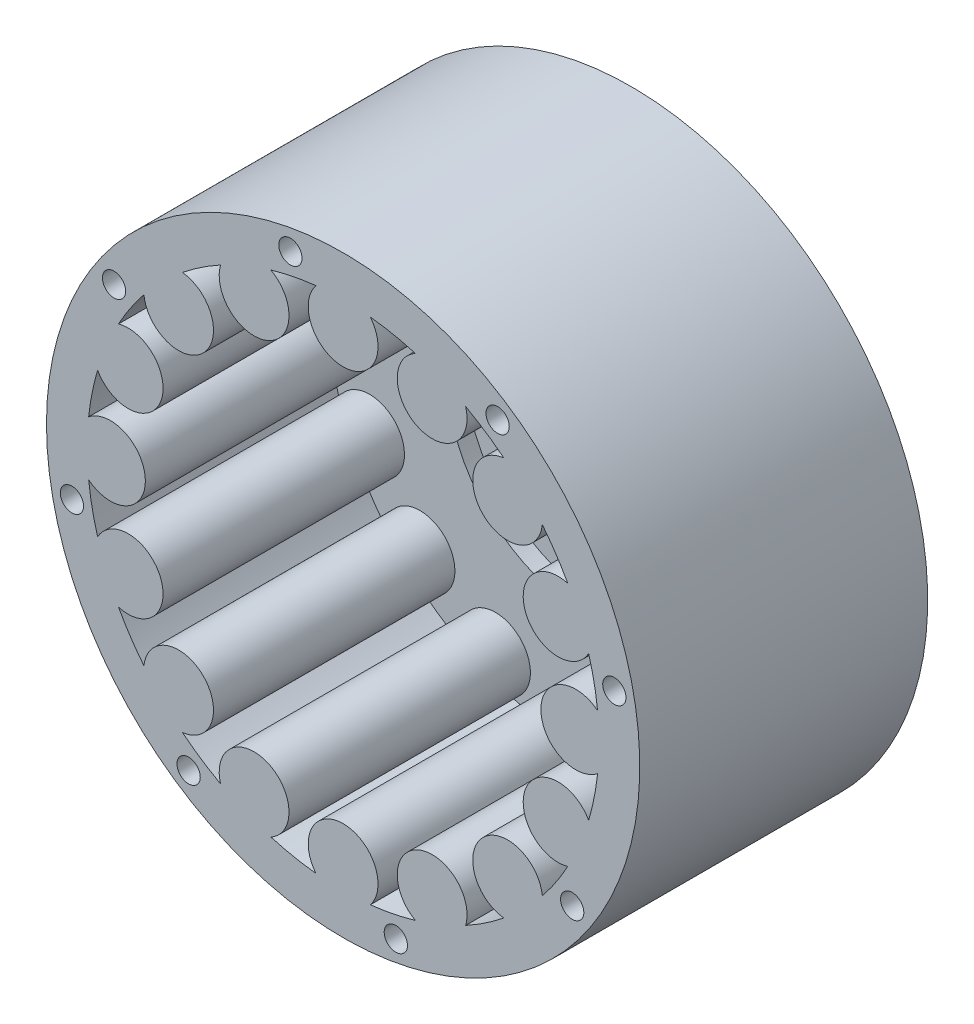
SolidWorks part; units mm, degrees
material "Custom Plastic"
ref_plane "Front Plane" through (0, 0, 0) normal (0, 0, 1) x (1, 0, 0)
ref_plane "Top Plane" through (0, 0, 0) normal (0, 1, 0) x (1, 0, 0)
ref_plane "Right Plane" through (0, 0, 0) normal (1, 0, 0) x (0, 0, -1)
sketch "Sketch1" plane through (0, 0, 0) normal (0, 0, 1) x (1, 0, 0)
  circle A2 centre (0, 0) radius 44
  dimension "D1" = 88
extrude "VolumeExtrude" add sketch "Sketch1" along normal blind 8
sketch "Sketch2" plane through (0, 0, 0) normal (0, 0, -1) x (-1, 0, 0)
  circle A1 centre (0, 0) radius 44 construction
  circle A2 centre (0, 0) radius 51
  circle A3 centre (0, 0) radius 51
  circle A4 centre (0, 0) radius 44
  dimension "D1" = 7
extrude "LipExtrude" add sketch "Sketch2" against normal blind 49.5
sketch "Sketch3" plane through (0, 0, 8) normal (0, 0, 1) x (1, 0, 0)
  circle A0 centre (0, 0) radius 40 construction
  circle A1 centre (0, 40) radius 6
  circle A2 centre (15.3073, 36.9552) radius 6
  circle A3 centre (28.2843, 28.2843) radius 6
  circle A4 centre (36.9552, 15.3073) radius 6
  circle A5 centre (40, 0) radius 6
  circle A6 centre (36.9552, -15.3073) radius 6
  circle A7 centre (28.2843, -28.2843) radius 6
  circle A8 centre (15.3073, -36.9552) radius 6
  circle A9 centre (0, -40) radius 6
  circle A10 centre (-15.3073, -36.9552) radius 6
  circle A11 centre (-28.2843, -28.2843) radius 6
  circle A12 centre (-36.9552, -15.3073) radius 6
  circle A13 centre (-40, 0) radius 6
  circle A14 centre (-36.9552, 15.3073) radius 6
  circle A15 centre (-28.2843, 28.2843) radius 6
  circle A16 centre (-15.3073, 36.9552) radius 6
  circle A18 centre (0, 0) radius 44 construction
  circle A19 centre (0, 0) radius 44 construction
  point P37 (0, 0)
  dimension "D1" = 80
  dimension "D2" = 12
  dimension "D3" = 16
extrude "EdgeCuts" [suppressed] cut sketch "Sketch3" along normal up to surface (24.5 mm away)
sketch "Sketch4" plane through (0, 0, 8) normal (0, 0, 1) x (1, 0, 0)
  circle A0 centre (0, 0) radius 18
  dimension "D1" = 36
extrude "Shaft Hole" cut sketch "Sketch4" against normal up to surface (8 mm away) contours A0 up to face at (-51, 0, 0)
sketch "Sketch5" [suppressed] plane through (0, 0, 7) normal (0, 0, 1) x (1, 0, 0)
  circle A0 centre (0, 0) radius 23.5
  dimension "D1" = 47
extrude "BearingHole" [suppressed] cut sketch "Sketch5" against normal blind 7
sketch "Sketch6" plane through (0, 0, 49.5) normal (0, 0, 1) x (1, 0, 0)
  line L0 (0, 0) -> (-9.0634, 46.6273) construction
  line L3 (0, 0) -> (25.3584, 0) construction
  circle A0 centre (-9.0634, 46.6273) radius 2
  circle A1 centre (26.5617, 39.3793) radius 2
  circle A2 centre (0, 0) radius 44 construction
  circle A3 centre (0, 0) radius 51 construction
  circle A4 centre (0, 0) radius 51 construction
  circle A5 centre (0, 0) radius 44 construction
  circle A13 centre (46.6273, 9.0634) radius 2
  circle A14 centre (39.3793, -26.5617) radius 2
  circle A15 centre (9.0634, -46.6273) radius 2
  circle A16 centre (-26.5617, -39.3793) radius 2
  circle A17 centre (-46.6273, -9.0634) radius 2
  circle A18 centre (-39.3793, 26.5617) radius 2
  point P23 (0, 0)
  point P31 (0, 0)
  dimension "D1" = 4
  dimension "D3" = 47.5
  dimension "D2" = 101
  dimension "D4" = 8
extrude "BoltHoles" cut sketch "Sketch6" against normal blind 6
sketch "Sketch7" plane through (0, 0, 8) normal (0, 0, 1) x (1, 0, 0)
  line L0 (0, 0) -> (0, 40) construction
  circle A0 centre (0, 40) radius 6
  circle A1 centre (15.3073, 36.9552) radius 6
  circle A2 centre (28.2843, 28.2843) radius 6
  circle A3 centre (36.9552, 15.3073) radius 6
  circle A4 centre (40, 0) radius 6
  circle A5 centre (36.9552, -15.3073) radius 6
  circle A6 centre (28.2843, -28.2843) radius 6
  circle A7 centre (15.3073, -36.9552) radius 6
  circle A8 centre (0, -40) radius 6
  circle A9 centre (-15.3073, -36.9552) radius 6
  circle A10 centre (-28.2843, -28.2843) radius 6
  circle A11 centre (-36.9552, -15.3073) radius 6
  circle A12 centre (-40, 0) radius 6
  circle A13 centre (-36.9552, 15.3073) radius 6
  circle A14 centre (-28.2843, 28.2843) radius 6
  circle A15 centre (-15.3073, 36.9552) radius 6
  point P36 (0, 0)
  dimension "D1" = 12
  dimension "D2" = 40
  dimension "D3" = 16
extrude "Boss-Extrude1" add sketch "Sketch7" along normal up to surface (41.5 mm away) up to face at (-7.0634, 46.6273, 49.5)
sketch "Sketch9" plane through (0, 0, 0) normal (0, 0, -1) x (-1, 0, 0)
  line L0 (0, 0) -> (-26.5617, 39.3793) construction
  line L1 (0, 0) -> (-52.3937, 0) construction
  circle A0 centre (0, 0) radius 47.5 construction
  circle A1 centre (-26.5617, 39.3793) radius 2.25
  circle A5 centre (39.3793, 26.5617) radius 2.25
  circle A6 centre (26.5617, -39.3793) radius 2.25
  circle A7 centre (-39.3793, -26.5617) radius 2.25
  circle A8 centre (-26.5617, 39.3793) radius 2 construction
  circle A9 centre (-26.5617, 39.3793) radius 2 construction
  point P12 (0, 0)
  point P16 (0, 0)
  dimension "D2" = 4.5
  dimension "D4" = 4
extrude "Cut-Extrude2" cut sketch "Sketch9" against normal blind 6
sketch "Sketch11" plane through (0, 0, 8) normal (0, 0, 1) x (1, 0, 0)
  circle A0 centre (0, 0) radius 23.6
  dimension "D1" = 47.2
extrude "Cut-Extrude3" cut sketch "Sketch11" against normal blind 3
